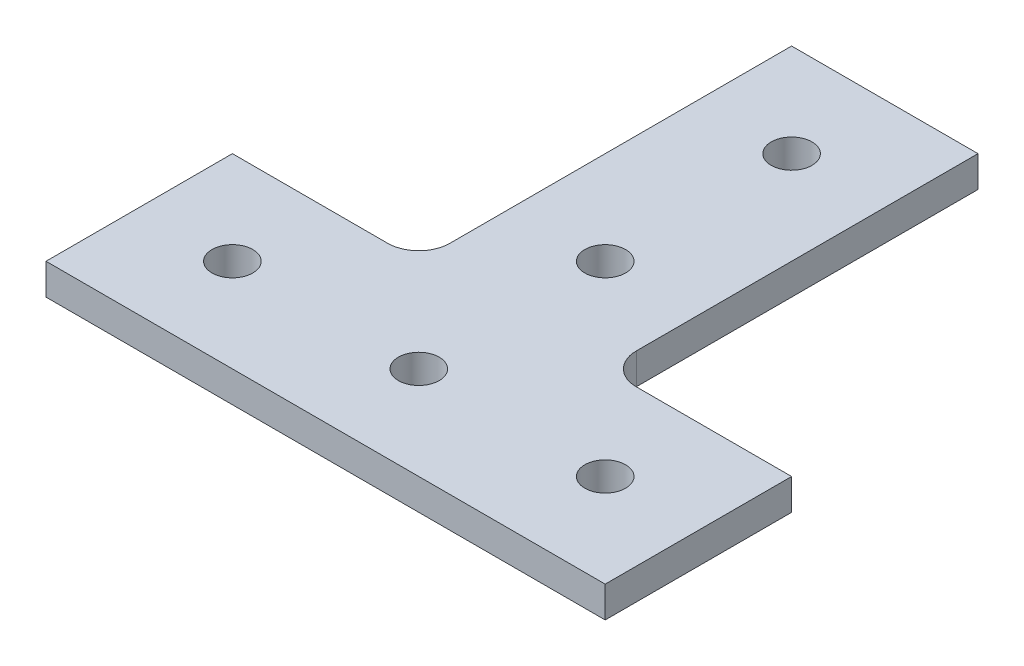
SolidWorks part; units mm, degrees
ref_plane "Front Plane" through (0, 0, 0) normal (0, 0, 1) x (1, 0, 0)
ref_plane "Top Plane" through (0, 0, 0) normal (0, 1, 0) x (1, 0, 0)
ref_plane "Right Plane" through (0, 0, 0) normal (1, 0, 0) x (0, 0, -1)
sketch "Sketch1" plane through (0, 0, 0) normal (0, 1, 0) x (1, 0, 0)
  line L0 (-77.2236, -17.6284) -> (-77.2236, 20.4716)
  line L1 (-77.2236, 20.4716) -> (-45.4736, 20.4716)
  line L2 (-39.1236, 26.8216) -> (-39.1236, 96.6716)
  line L3 (-39.1236, 96.6716) -> (-1.0236, 96.6716)
  line L4 (-1.0236, 96.6716) -> (-1.0236, 26.8216)
  line L5 (5.3264, 20.4716) -> (37.0764, 20.4716)
  line L6 (37.0764, 20.4716) -> (37.0764, -17.6284)
  line L7 (37.0764, -17.6284) -> (-77.2236, -17.6284)
  arc A0 (-45.4736, 20.4716) -> (-39.1236, 26.8216) centre (-45.4736, 26.8216) ccw
  arc A1 (5.3264, 20.4716) -> (-1.0236, 26.8216) centre (5.3264, 26.8216) cw
  circle A2 centre (-20.0736, 77.6216) radius 4.1656
  circle A3 centre (-20.0736, 39.5216) radius 4.1656
  circle A4 centre (-20.0736, 1.4216) radius 4.1656
  circle A5 centre (18.0264, 1.4216) radius 4.1656
  circle A6 centre (-58.1736, 1.4216) radius 4.1656
  point P10 (-39.1236, 20.4716)
  dimension "D6" = 6.35
  dimension "D7" = 6.35
  dimension "D8" = 19.05
  dimension "D10" = 38.1
  dimension "D11" = 8.3312
  dimension "D13" = 38.1
  dimension "D16" = 38.1
  dimension "D1" = 38.1
  dimension "D2" = 114.3
  dimension "D3" = 38.1
  dimension "D4" = 114.3
  dimension "D5" = 38.1
  dimension "D9" = 19.05
  dimension "D12" = 38.1
  dimension "D14" = 19.05
  dimension "D15" = 19.05
  dimension "D17" = 19.05
extrude "Boss-Extrude2" add sketch "Sketch1" along normal blind 6.35
